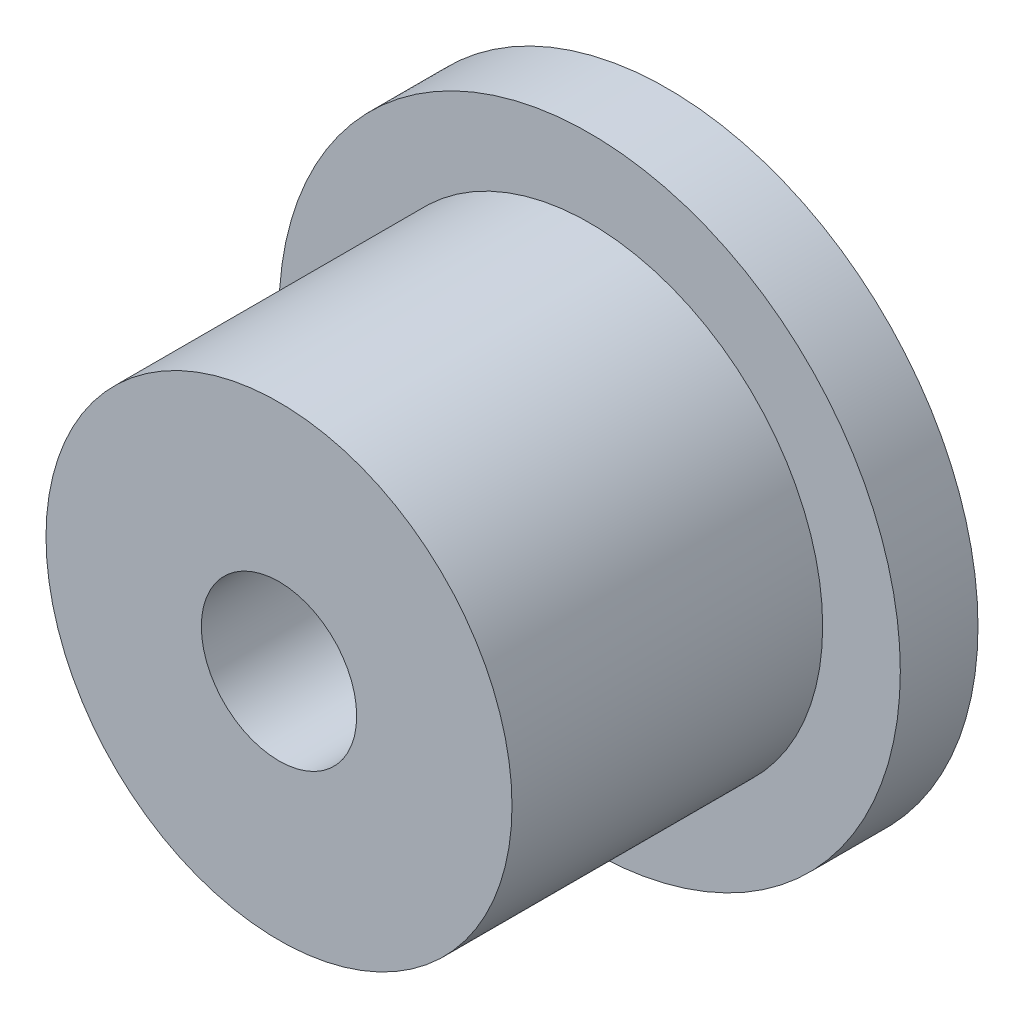
SolidWorks part; units mm, degrees
ref_plane "Front Plane" through (0, 0, 0) normal (0, 0, 1) x (1, 0, 0)
ref_plane "Top Plane" through (0, 0, 0) normal (0, 1, 0) x (1, 0, 0)
ref_plane "Right Plane" through (0, 0, 0) normal (1, 0, 0) x (0, 0, -1)
sketch "Sketch1" plane through (0, 0, 0) normal (0, 0, 1) x (1, 0, 0)
  circle A0 centre (0, 0) radius 75
  circle A1 centre (0, 0) radius 25
  dimension "D1" = 150
  dimension "D2" = 50
extrude "Boss-Extrude1" add sketch "Sketch1" along normal blind 100
sketch "Sketch2" plane through (0, 0, 0) normal (0, 0, -1) x (-1, 0, 0)
  circle A0 centre (0, 0) radius 100
  circle A1 centre (0, 0) radius 25 construction
  circle A2 centre (0, 0) radius 25
  dimension "D1" = 200
extrude "Boss-Extrude3" add sketch "Sketch2" along normal blind 25
